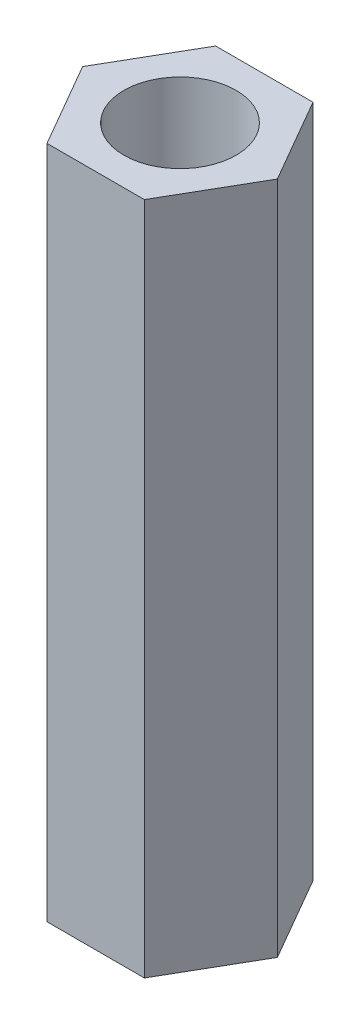
SolidWorks part; units mm, degrees
material "黄铜"
ref_plane "前视基准面" through (0, 0, 0) normal (0, 0, 1) x (1, 0, 0)
ref_plane "上视基准面" through (0, 0, 0) normal (0, 1, 0) x (1, 0, 0)
ref_plane "右视基准面" through (0, 0, 0) normal (1, 0, 0) x (0, 0, -1)
other "Configuration Table"
sketch "草图1" plane through (0, 0, 0) normal (0, 1, 0) x (1, 0, 0)
  line L1 (2.6, 0) -> (1.3, 2.2517)
  line L2 (1.3, 2.2517) -> (-1.3, 2.2517)
  line L3 (-1.3, 2.2517) -> (-2.6, 0)
  line L4 (-2.6, 0) -> (-1.3, -2.2517)
  line L5 (-1.3, -2.2517) -> (1.3, -2.2517)
  line L6 (1.3, -2.2517) -> (2.6, 0)
  circle A0 centre (0, 0) radius 2.2517 construction
  circle A1 centre (0, 0) radius 1.5
  dimension "D1" = 5.2
  dimension "D2" = 4.5033
extrude "凸台-拉伸1" add sketch "草图1" along normal blind 18
